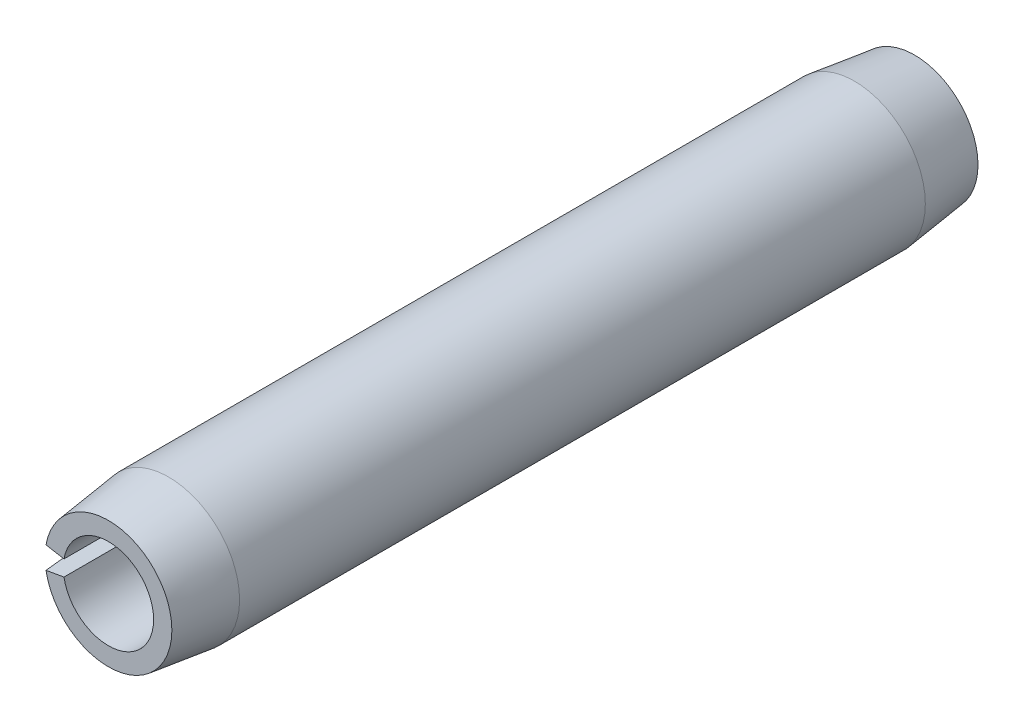
SolidWorks part; units mm, degrees
ref_plane "Front Plane" through (0, 0, 0) normal (0, 0, 1) x (1, 0, 0)
ref_plane "Top Plane" through (0, 0, 0) normal (0, 1, 0) x (1, 0, 0)
ref_plane "Right Plane" through (0, 0, 0) normal (1, 0, 0) x (0, 0, -1)
sketch "Sketch1" plane through (0, 0, 0) normal (0, 0, 1) x (1, 0, 0)
  line L0 (0.5334, 0) -> (0.8382, 0) construction
  line L1 (-0.8255, 0.1456) -> (-0.5253, 0.0926)
  line L2 (-0.5253, -0.0926) -> (-0.8255, -0.1456)
  arc A0 (-0.8255, -0.1456) -> (-0.8255, 0.1456) centre (0, 0) ccw
  arc A1 (-0.5253, -0.0926) -> (-0.5253, 0.0926) centre (0, 0) ccw
  dimension "OD" = 1.6764
  dimension "Wall thickness" = 0.3048
  dimension "D3" = 20
extrude "Extrude1" add sketch "Sketch1" along normal mid plane 9.525
sketch "Sketch2" plane through (0, 0, 0) normal (1, 0, 0) x (0, 0, -1)
  line L0 (0, -0.8382) -> (0, 0.8382) construction
  line L1 (4.7625, 0) -> (-4.7625, 0) construction
  line L2 (4.7625, -0.5334) -> (4.7625, 0.5334) construction
  line L3 (4.7625, 0.8382) -> (-4.7625, 0.8382) construction
  line L4 (4.7625, 0.8382) -> (4.7625, 0.7493)
  line L5 (4.7625, 0.7493) -> (4.0513, 0.8382)
  line L6 (4.0513, 0.8382) -> (4.7625, 0.8382)
  line L7 (4.7625, -0.8382) -> (4.7625, 0.8382) construction
  line L8 (-4.0513, 0.8382) -> (-4.7625, 0.8382)
  line L9 (-4.7625, 0.7493) -> (-4.0513, 0.8382)
  line L10 (-4.7625, 0.8382) -> (-4.7625, 0.7493)
  line L11 (4.0513, -0.8382) -> (4.7625, -0.8382) construction
  line L12 (4.7625, -0.7493) -> (4.0513, -0.8382) construction
  line L13 (4.7625, -0.8382) -> (4.7625, -0.7493) construction
  dimension "B" = 1.4986
  dimension "Chamfer max" = 0.7112
revolve "Cut-Revolve1" cut sketch "Sketch2" angle 360 about L1
sketch "Sketch3" plane through (0, 0, 0) normal (0, 0, 1) x (1, 0, 0)
  line L0 (0.5334, 0) -> (0.8382, 0) construction
  line L1 (0.5334, 0) -> (0.8382, 0)
  circle A0 centre (0, 0) radius 0.8382
  circle A1 centre (0, 0) radius 0.5334
  arc A2 (-0.8255, -0.1456) -> (-0.8255, 0.1456) centre (0, 0) ccw construction
  arc A3 (-0.5253, -0.0926) -> (-0.5253, 0.0926) centre (0, 0) ccw construction
